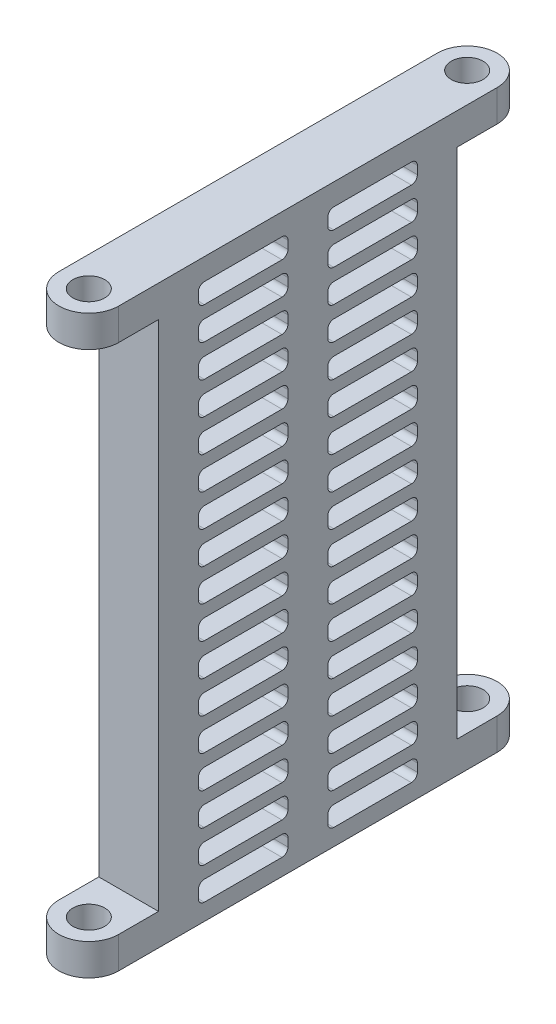
SolidWorks part; units mm, degrees
ref_plane "Front Plane" through (0, 0, 0) normal (0, 0, 1) x (1, 0, 0)
ref_plane "Top Plane" through (0, 0, 0) normal (0, 1, 0) x (1, 0, 0)
ref_plane "Right Plane" through (0, 0, 0) normal (1, 0, 0) x (0, 0, -1)
sketch "Sketch2" plane through (0, 0, 0) normal (0, 1, 0) x (1, 0, 0)
  line L0 (-3, 0) -> (-3, -38)
  line L1 (3, -38) -> (3, 0)
  arc A0 (3, 0) -> (-3, 0) centre (0, 0) ccw
  arc A1 (-3, -38) -> (3, -38) centre (0, -38) ccw
  circle A2 centre (0, 0) radius 1.6
  circle A3 centre (0, -38) radius 1.6
  dimension "D1" = 3.2
  dimension "D2" = 3
  dimension "D3" = 38
extrude "Boss-Extrude1" add sketch "Sketch2" along normal blind 3.175
sketch "Sketch3" plane through (0, 3.175, 0) normal (0, 1, 0) x (1, 0, 0)
  line L0 (-3, 0) -> (-3, -38) construction
  line L1 (-3, -4) -> (3, -4)
  line L2 (-3, -4) -> (-3, -34)
  line L3 (-3, -34) -> (3, -34)
  line L4 (3, -4) -> (3, -34)
  line L5 (3, -38) -> (3, 0) construction
  circle A0 centre (0, -38) radius 1.6 construction
  point P9 (0, -34)
  dimension "D1" = 4
  dimension "D2" = 4
extrude "Boss-Extrude2" add sketch "Sketch3" along normal blind 51.48
ref_plane "Plane1" through (0, 28.915, 0) normal (0, 1, 0) x (1, 0, 0)
mirror "Mirror2" about plane through (0, 28.915, 0) normal (0, 1, 0) of "Boss-Extrude1"
sketch "Sketch4" plane through (3, 0, 0) normal (1, 0, 0) x (0, 0, -1)
  line L0 (-4, 54.655) -> (-34, 54.655) construction
  line L1 (-8.6, 13.4236) -> (-16.4, 13.4236)
  line L2 (-8, 12.8236) -> (-8, 12.0236)
  line L3 (-4, 3.175) -> (-34, 3.175) construction
  line L4 (-8.6, 11.4236) -> (-16.4, 11.4236)
  line L5 (-17, 12.8236) -> (-17, 12.0236)
  line L11 (-19, 57.83) -> (-19, 0) construction
  line L12 (-38, 57.83) -> (0, 57.83) construction
  line L24 (-38, 0) -> (0, 0) construction
  line L25 (-4, 54.655) -> (-4, 3.175) construction
  line L30 (-8.6, 55.655) -> (-16.4, 55.655)
  line L39 (-8, 55.055) -> (-8, 54.255)
  line L40 (-8.6, 53.655) -> (-16.4, 53.655)
  line L41 (-17, 55.055) -> (-17, 54.255)
  line L46 (-8, 55.655) -> (-17, 53.655) construction
  line L47 (-8, 53.655) -> (-17, 55.655) construction
  line L64 (-8.6, 52.4064) -> (-16.4, 52.4064)
  line L69 (-8, 51.8064) -> (-8, 51.0064)
  line L70 (-8.6, 50.4064) -> (-16.4, 50.4064)
  line L71 (-17, 51.8064) -> (-17, 51.0064)
  line L72 (-4, 51.4064) -> (-34, 51.4064) construction
  line L73 (-8, 52.4064) -> (-17, 50.4064) construction
  line L74 (-8, 50.4064) -> (-17, 52.4064) construction
  line L75 (-8.6, 49.1579) -> (-16.4, 49.1579)
  line L76 (-8, 48.5579) -> (-8, 47.7579)
  line L77 (-8.6, 47.1579) -> (-16.4, 47.1579)
  line L78 (-17, 48.5579) -> (-17, 47.7579)
  line L79 (-4, 48.1579) -> (-34, 48.1579) construction
  line L132 (-8, 49.1579) -> (-17, 47.1579) construction
  line L133 (-8, 47.1579) -> (-17, 49.1579) construction
  line L134 (-8.6, 45.9093) -> (-16.4, 45.9093)
  line L135 (-8, 45.3093) -> (-8, 44.5093)
  line L136 (-8.6, 43.9093) -> (-16.4, 43.9093)
  line L137 (-17, 45.3093) -> (-17, 44.5093)
  line L138 (-4, 44.9093) -> (-34, 44.9093) construction
  line L139 (-8, 45.9093) -> (-17, 43.9093) construction
  line L140 (-8, 43.9093) -> (-17, 45.9093) construction
  line L141 (-8.6, 42.6607) -> (-16.4, 42.6607)
  line L142 (-8, 42.0607) -> (-8, 41.2607)
  line L143 (-8.6, 40.6607) -> (-16.4, 40.6607)
  line L144 (-17, 42.0607) -> (-17, 41.2607)
  line L145 (-4, 41.6607) -> (-34, 41.6607) construction
  line L146 (-8, 42.6607) -> (-17, 40.6607) construction
  line L147 (-8, 40.6607) -> (-17, 42.6607) construction
  line L148 (-8.6, 39.4121) -> (-16.4, 39.4121)
  line L149 (-8, 38.8121) -> (-8, 38.0121)
  line L186 (-4, 12.4236) -> (-34, 12.4236) construction
  line L187 (-8, 13.4236) -> (-17, 11.4236) construction
  line L188 (-8, 11.4236) -> (-17, 13.4236) construction
  line L189 (-8.6, 10.175) -> (-16.4, 10.175)
  line L190 (-8, 9.575) -> (-8, 8.775)
  line L191 (-8.6, 8.175) -> (-16.4, 8.175)
  line L192 (-17, 9.575) -> (-17, 8.775)
  line L193 (-4, 9.175) -> (-34, 9.175) construction
  line L194 (-8, 10.175) -> (-17, 8.175) construction
  line L195 (-8, 8.175) -> (-17, 10.175) construction
  line L196 (-30, 1.6779) -> (-21, 3.6779) construction
  line L197 (-30, 3.6779) -> (-21, 1.6779) construction
  line L198 (-30, 4.9264) -> (-21, 6.9264) construction
  line L199 (-30, 6.9264) -> (-21, 4.9264) construction
  line L200 (-30, 14.6721) -> (-21, 16.6721) construction
  line L201 (-8.6, 37.4121) -> (-16.4, 37.4121)
  line L202 (-17, 38.8121) -> (-17, 38.0121)
  line L203 (-4, 38.4121) -> (-34, 38.4121) construction
  line L204 (-8, 39.4121) -> (-17, 37.4121) construction
  line L205 (-8, 37.4121) -> (-17, 39.4121) construction
  line L206 (-8.6, 36.1636) -> (-16.4, 36.1636)
  line L207 (-8, 35.5636) -> (-8, 34.7636)
  line L208 (-8.6, 34.1636) -> (-16.4, 34.1636)
  line L209 (-17, 35.5636) -> (-17, 34.7636)
  line L210 (-4, 35.1636) -> (-34, 35.1636) construction
  line L211 (-8, 36.1636) -> (-17, 34.1636) construction
  line L212 (-8, 34.1636) -> (-17, 36.1636) construction
  line L213 (-8.6, 32.915) -> (-16.4, 32.915)
  line L214 (-8, 32.315) -> (-8, 31.515)
  line L215 (-8.6, 30.915) -> (-16.4, 30.915)
  line L216 (-17, 32.315) -> (-17, 31.515)
  line L217 (-4, 31.915) -> (-34, 31.915) construction
  line L218 (-8, 32.915) -> (-17, 30.915) construction
  line L219 (-8, 30.915) -> (-17, 32.915) construction
  line L220 (-8.6, 29.6664) -> (-16.4, 29.6664)
  line L221 (-8, 29.0664) -> (-8, 28.2664)
  line L222 (-8.6, 27.6664) -> (-16.4, 27.6664)
  line L223 (-17, 29.0664) -> (-17, 28.2664)
  line L224 (-4, 28.6664) -> (-34, 28.6664) construction
  line L225 (-8, 29.6664) -> (-17, 27.6664) construction
  line L226 (-8, 27.6664) -> (-17, 29.6664) construction
  line L227 (-8.6, 26.4179) -> (-16.4, 26.4179)
  line L228 (-8, 25.8179) -> (-8, 25.0179)
  line L229 (-8.6, 24.4179) -> (-16.4, 24.4179)
  line L230 (-17, 25.8179) -> (-17, 25.0179)
  line L231 (-4, 25.4179) -> (-34, 25.4179) construction
  line L232 (-8, 26.4179) -> (-17, 24.4179) construction
  line L233 (-8, 24.4179) -> (-17, 26.4179) construction
  line L234 (-8.6, 23.1693) -> (-16.4, 23.1693)
  line L235 (-8, 22.5693) -> (-8, 21.7693)
  line L236 (-8.6, 21.1693) -> (-16.4, 21.1693)
  line L237 (-17, 22.5693) -> (-17, 21.7693)
  line L238 (-4, 22.1693) -> (-34, 22.1693) construction
  line L239 (-8, 23.1693) -> (-17, 21.1693) construction
  line L240 (-8, 21.1693) -> (-17, 23.1693) construction
  line L241 (-8.6, 19.9207) -> (-16.4, 19.9207)
  line L242 (-8, 19.3207) -> (-8, 18.5207)
  line L243 (-8.6, 17.9207) -> (-16.4, 17.9207)
  line L244 (-17, 19.3207) -> (-17, 18.5207)
  line L245 (-4, 18.9207) -> (-34, 18.9207) construction
  line L246 (-8, 19.9207) -> (-17, 17.9207) construction
  line L247 (-8, 17.9207) -> (-17, 19.9207) construction
  line L248 (-8.6, 16.6721) -> (-16.4, 16.6721)
  line L249 (-8, 16.0721) -> (-8, 15.2721)
  line L250 (-8.6, 14.6721) -> (-16.4, 14.6721)
  line L251 (-17, 16.0721) -> (-17, 15.2721)
  line L252 (-4, 15.6721) -> (-34, 15.6721) construction
  line L253 (-8, 16.6721) -> (-17, 14.6721) construction
  line L254 (-8, 14.6721) -> (-17, 16.6721) construction
  line L255 (-30, 16.6721) -> (-21, 14.6721) construction
  line L256 (-30, 17.9207) -> (-21, 19.9207) construction
  line L257 (-30, 19.9207) -> (-21, 17.9207) construction
  line L258 (-30, 21.1693) -> (-21, 23.1693) construction
  line L259 (-30, 23.1693) -> (-21, 21.1693) construction
  line L260 (-30, 24.4179) -> (-21, 26.4179) construction
  line L261 (-30, 26.4179) -> (-21, 24.4179) construction
  line L262 (-30, 27.6664) -> (-21, 29.6664) construction
  line L263 (-30, 29.6664) -> (-21, 27.6664) construction
  line L264 (-30, 30.915) -> (-21, 32.915) construction
  line L265 (-30, 32.915) -> (-21, 30.915) construction
  line L266 (-30, 34.1636) -> (-21, 36.1636) construction
  line L267 (-30, 36.1636) -> (-21, 34.1636) construction
  line L268 (-30, 37.4121) -> (-21, 39.4121) construction
  line L269 (-30, 39.4121) -> (-21, 37.4121) construction
  line L270 (-30, 8.175) -> (-21, 10.175) construction
  line L271 (-30, 10.175) -> (-21, 8.175) construction
  line L272 (-30, 11.4236) -> (-21, 13.4236) construction
  line L273 (-30, 13.4236) -> (-21, 11.4236) construction
  line L274 (-30, 40.6607) -> (-21, 42.6607) construction
  line L275 (-30, 42.6607) -> (-21, 40.6607) construction
  line L276 (-30, 43.9093) -> (-21, 45.9093) construction
  line L277 (-30, 45.9093) -> (-21, 43.9093) construction
  line L278 (-30, 47.1579) -> (-21, 49.1579) construction
  line L279 (-30, 49.1579) -> (-21, 47.1579) construction
  line L392 (-8.6, 6.9264) -> (-16.4, 6.9264)
  line L393 (-8, 6.3264) -> (-8, 5.5264)
  line L394 (-8.6, 4.9264) -> (-16.4, 4.9264)
  line L395 (-17, 6.3264) -> (-17, 5.5264)
  line L396 (-4, 5.9264) -> (-34, 5.9264) construction
  line L397 (-8, 6.9264) -> (-17, 4.9264) construction
  line L398 (-8, 4.9264) -> (-17, 6.9264) construction
  line L399 (-8.6, 3.6779) -> (-16.4, 3.6779)
  line L400 (-8, 3.0779) -> (-8, 2.2779)
  line L401 (-8.6, 1.6779) -> (-16.4, 1.6779)
  line L402 (-17, 3.0779) -> (-17, 2.2779)
  line L403 (-4, 2.6779) -> (-34, 2.6779) construction
  line L404 (-8, 3.6779) -> (-17, 1.6779) construction
  line L405 (-8, 1.6779) -> (-17, 3.6779) construction
  line L406 (-30, 50.4064) -> (-21, 52.4064) construction
  line L407 (-30, 52.4064) -> (-21, 50.4064) construction
  line L408 (-30, 53.655) -> (-21, 55.655) construction
  line L409 (-30, 55.655) -> (-21, 53.655) construction
  line L410 (-21, 3.0779) -> (-21, 2.2779)
  line L411 (-29.4, 1.6779) -> (-21.6, 1.6779)
  line L412 (-30, 3.0779) -> (-30, 2.2779)
  line L413 (-29.4, 3.6779) -> (-21.6, 3.6779)
  line L414 (-21, 6.3264) -> (-21, 5.5264)
  line L415 (-29.4, 4.9264) -> (-21.6, 4.9264)
  line L416 (-30, 6.3264) -> (-30, 5.5264)
  line L417 (-29.4, 6.9264) -> (-21.6, 6.9264)
  line L418 (-21, 16.0721) -> (-21, 15.2721)
  line L419 (-29.4, 14.6721) -> (-21.6, 14.6721)
  line L420 (-30, 16.0721) -> (-30, 15.2721)
  line L421 (-29.4, 16.6721) -> (-21.6, 16.6721)
  line L422 (-21, 19.3207) -> (-21, 18.5207)
  line L423 (-29.4, 17.9207) -> (-21.6, 17.9207)
  line L424 (-30, 19.3207) -> (-30, 18.5207)
  line L425 (-29.4, 19.9207) -> (-21.6, 19.9207)
  line L426 (-21, 22.5693) -> (-21, 21.7693)
  line L427 (-29.4, 21.1693) -> (-21.6, 21.1693)
  line L428 (-30, 22.5693) -> (-30, 21.7693)
  line L429 (-29.4, 23.1693) -> (-21.6, 23.1693)
  line L430 (-21, 25.8179) -> (-21, 25.0179)
  line L431 (-29.4, 24.4179) -> (-21.6, 24.4179)
  line L432 (-30, 25.8179) -> (-30, 25.0179)
  line L433 (-29.4, 26.4179) -> (-21.6, 26.4179)
  line L434 (-21, 29.0664) -> (-21, 28.2664)
  line L435 (-29.4, 27.6664) -> (-21.6, 27.6664)
  line L436 (-30, 29.0664) -> (-30, 28.2664)
  line L437 (-29.4, 29.6664) -> (-21.6, 29.6664)
  line L438 (-21, 32.315) -> (-21, 31.515)
  line L439 (-29.4, 30.915) -> (-21.6, 30.915)
  line L440 (-30, 32.315) -> (-30, 31.515)
  line L441 (-29.4, 32.915) -> (-21.6, 32.915)
  line L442 (-21, 35.5636) -> (-21, 34.7636)
  line L443 (-29.4, 34.1636) -> (-21.6, 34.1636)
  line L444 (-30, 35.5636) -> (-30, 34.7636)
  line L445 (-29.4, 36.1636) -> (-21.6, 36.1636)
  line L446 (-21, 38.8121) -> (-21, 38.0121)
  line L447 (-29.4, 37.4121) -> (-21.6, 37.4121)
  line L448 (-21, 9.575) -> (-21, 8.775)
  line L449 (-29.4, 8.175) -> (-21.6, 8.175)
  line L450 (-30, 9.575) -> (-30, 8.775)
  line L451 (-29.4, 10.175) -> (-21.6, 10.175)
  line L452 (-30, 38.8121) -> (-30, 38.0121)
  line L453 (-29.4, 39.4121) -> (-21.6, 39.4121)
  line L454 (-21, 42.0607) -> (-21, 41.2607)
  line L455 (-29.4, 40.6607) -> (-21.6, 40.6607)
  line L456 (-30, 42.0607) -> (-30, 41.2607)
  line L457 (-29.4, 42.6607) -> (-21.6, 42.6607)
  line L458 (-21, 45.3093) -> (-21, 44.5093)
  line L459 (-29.4, 43.9093) -> (-21.6, 43.9093)
  line L460 (-30, 45.3093) -> (-30, 44.5093)
  line L461 (-29.4, 45.9093) -> (-21.6, 45.9093)
  line L462 (-21, 48.5579) -> (-21, 47.7579)
  line L463 (-29.4, 47.1579) -> (-21.6, 47.1579)
  line L464 (-30, 48.5579) -> (-30, 47.7579)
  line L465 (-29.4, 49.1579) -> (-21.6, 49.1579)
  line L466 (-21, 51.8064) -> (-21, 51.0064)
  line L467 (-29.4, 50.4064) -> (-21.6, 50.4064)
  line L468 (-30, 51.8064) -> (-30, 51.0064)
  line L469 (-29.4, 52.4064) -> (-21.6, 52.4064)
  line L470 (-21, 55.055) -> (-21, 54.255)
  line L471 (-29.4, 53.655) -> (-21.6, 53.655)
  line L472 (-30, 55.055) -> (-30, 54.255)
  line L473 (-29.4, 55.655) -> (-21.6, 55.655)
  line L474 (-21, 12.8236) -> (-21, 12.0236)
  line L475 (-29.4, 11.4236) -> (-21.6, 11.4236)
  line L476 (-30, 12.8236) -> (-30, 12.0236)
  line L477 (-29.4, 13.4236) -> (-21.6, 13.4236)
  arc A72 (-16.4, 13.4236) -> (-17, 12.8236) centre (-16.4, 12.8236) ccw
  arc A73 (-16.4, 11.4236) -> (-17, 12.0236) centre (-16.4, 12.0236) cw
  arc A74 (-8.6, 13.4236) -> (-8, 12.8236) centre (-8.6, 12.8236) cw
  arc A75 (-8, 12.0236) -> (-8.6, 11.4236) centre (-8.6, 12.0236) cw
  arc A76 (-16.4, 55.655) -> (-17, 55.055) centre (-16.4, 55.055) ccw
  arc A77 (-16.4, 53.655) -> (-17, 54.255) centre (-16.4, 54.255) cw
  arc A78 (-8.6, 55.655) -> (-8, 55.055) centre (-8.6, 55.055) cw
  arc A79 (-8, 54.255) -> (-8.6, 53.655) centre (-8.6, 54.255) cw
  arc A80 (-16.4, 52.4064) -> (-17, 51.8064) centre (-16.4, 51.8064) ccw
  arc A81 (-16.4, 50.4064) -> (-17, 51.0064) centre (-16.4, 51.0064) cw
  arc A82 (-8.6, 52.4064) -> (-8, 51.8064) centre (-8.6, 51.8064) cw
  arc A83 (-8, 51.0064) -> (-8.6, 50.4064) centre (-8.6, 51.0064) cw
  arc A84 (-16.4, 49.1579) -> (-17, 48.5579) centre (-16.4, 48.5579) ccw
  arc A85 (-16.4, 47.1579) -> (-17, 47.7579) centre (-16.4, 47.7579) cw
  arc A86 (-8.6, 49.1579) -> (-8, 48.5579) centre (-8.6, 48.5579) cw
  arc A87 (-8, 47.7579) -> (-8.6, 47.1579) centre (-8.6, 47.7579) cw
  arc A88 (-16.4, 45.9093) -> (-17, 45.3093) centre (-16.4, 45.3093) ccw
  arc A89 (-16.4, 43.9093) -> (-17, 44.5093) centre (-16.4, 44.5093) cw
  arc A90 (-8.6, 45.9093) -> (-8, 45.3093) centre (-8.6, 45.3093) cw
  arc A91 (-8, 44.5093) -> (-8.6, 43.9093) centre (-8.6, 44.5093) cw
  arc A92 (-16.4, 42.6607) -> (-17, 42.0607) centre (-16.4, 42.0607) ccw
  arc A93 (-16.4, 40.6607) -> (-17, 41.2607) centre (-16.4, 41.2607) cw
  arc A94 (-8.6, 42.6607) -> (-8, 42.0607) centre (-8.6, 42.0607) cw
  arc A95 (-8, 41.2607) -> (-8.6, 40.6607) centre (-8.6, 41.2607) cw
  arc A96 (-16.4, 39.4121) -> (-17, 38.8121) centre (-16.4, 38.8121) ccw
  arc A97 (-16.4, 37.4121) -> (-17, 38.0121) centre (-16.4, 38.0121) cw
  arc A98 (-8.6, 39.4121) -> (-8, 38.8121) centre (-8.6, 38.8121) cw
  arc A99 (-8, 38.0121) -> (-8.6, 37.4121) centre (-8.6, 38.0121) cw
  arc A100 (-16.4, 36.1636) -> (-17, 35.5636) centre (-16.4, 35.5636) ccw
  arc A101 (-16.4, 34.1636) -> (-17, 34.7636) centre (-16.4, 34.7636) cw
  arc A102 (-8.6, 36.1636) -> (-8, 35.5636) centre (-8.6, 35.5636) cw
  arc A103 (-8, 34.7636) -> (-8.6, 34.1636) centre (-8.6, 34.7636) cw
  arc A104 (-16.4, 32.915) -> (-17, 32.315) centre (-16.4, 32.315) ccw
  arc A105 (-16.4, 30.915) -> (-17, 31.515) centre (-16.4, 31.515) cw
  arc A106 (-8.6, 32.915) -> (-8, 32.315) centre (-8.6, 32.315) cw
  arc A107 (-8, 31.515) -> (-8.6, 30.915) centre (-8.6, 31.515) cw
  arc A108 (-16.4, 29.6664) -> (-17, 29.0664) centre (-16.4, 29.0664) ccw
  arc A109 (-16.4, 27.6664) -> (-17, 28.2664) centre (-16.4, 28.2664) cw
  arc A110 (-8.6, 29.6664) -> (-8, 29.0664) centre (-8.6, 29.0664) cw
  arc A111 (-8, 28.2664) -> (-8.6, 27.6664) centre (-8.6, 28.2664) cw
  arc A112 (-16.4, 26.4179) -> (-17, 25.8179) centre (-16.4, 25.8179) ccw
  arc A113 (-16.4, 24.4179) -> (-17, 25.0179) centre (-16.4, 25.0179) cw
  arc A114 (-8.6, 26.4179) -> (-8, 25.8179) centre (-8.6, 25.8179) cw
  arc A115 (-8, 25.0179) -> (-8.6, 24.4179) centre (-8.6, 25.0179) cw
  arc A116 (-16.4, 23.1693) -> (-17, 22.5693) centre (-16.4, 22.5693) ccw
  arc A117 (-16.4, 21.1693) -> (-17, 21.7693) centre (-16.4, 21.7693) cw
  arc A118 (-8.6, 23.1693) -> (-8, 22.5693) centre (-8.6, 22.5693) cw
  arc A119 (-8, 21.7693) -> (-8.6, 21.1693) centre (-8.6, 21.7693) cw
  arc A120 (-16.4, 19.9207) -> (-17, 19.3207) centre (-16.4, 19.3207) ccw
  arc A121 (-16.4, 17.9207) -> (-17, 18.5207) centre (-16.4, 18.5207) cw
  arc A122 (-8.6, 19.9207) -> (-8, 19.3207) centre (-8.6, 19.3207) cw
  arc A123 (-8, 18.5207) -> (-8.6, 17.9207) centre (-8.6, 18.5207) cw
  arc A124 (-16.4, 16.6721) -> (-17, 16.0721) centre (-16.4, 16.0721) ccw
  arc A125 (-16.4, 14.6721) -> (-17, 15.2721) centre (-16.4, 15.2721) cw
  arc A126 (-8.6, 16.6721) -> (-8, 16.0721) centre (-8.6, 16.0721) cw
  arc A127 (-8, 15.2721) -> (-8.6, 14.6721) centre (-8.6, 15.2721) cw
  arc A180 (-16.4, 10.175) -> (-17, 9.575) centre (-16.4, 9.575) ccw
  arc A181 (-16.4, 8.175) -> (-17, 8.775) centre (-16.4, 8.775) cw
  arc A182 (-8.6, 10.175) -> (-8, 9.575) centre (-8.6, 9.575) cw
  arc A183 (-8, 8.775) -> (-8.6, 8.175) centre (-8.6, 8.775) cw
  arc A244 (-16.4, 6.9264) -> (-17, 6.3264) centre (-16.4, 6.3264) ccw
  arc A245 (-16.4, 4.9264) -> (-17, 5.5264) centre (-16.4, 5.5264) cw
  arc A246 (-8.6, 6.9264) -> (-8, 6.3264) centre (-8.6, 6.3264) cw
  arc A247 (-8, 5.5264) -> (-8.6, 4.9264) centre (-8.6, 5.5264) cw
  arc A248 (-16.4, 3.6779) -> (-17, 3.0779) centre (-16.4, 3.0779) ccw
  arc A249 (-16.4, 1.6779) -> (-17, 2.2779) centre (-16.4, 2.2779) cw
  arc A250 (-8.6, 3.6779) -> (-8, 3.0779) centre (-8.6, 3.0779) cw
  arc A251 (-8, 2.2779) -> (-8.6, 1.6779) centre (-8.6, 2.2779) cw
  arc A252 (-30, 2.2779) -> (-29.4, 1.6779) centre (-29.4, 2.2779) ccw
  arc A253 (-29.4, 3.6779) -> (-30, 3.0779) centre (-29.4, 3.0779) ccw
  arc A254 (-21.6, 1.6779) -> (-21, 2.2779) centre (-21.6, 2.2779) ccw
  arc A255 (-21.6, 3.6779) -> (-21, 3.0779) centre (-21.6, 3.0779) cw
  arc A256 (-30, 5.5264) -> (-29.4, 4.9264) centre (-29.4, 5.5264) ccw
  arc A257 (-29.4, 6.9264) -> (-30, 6.3264) centre (-29.4, 6.3264) ccw
  arc A258 (-21.6, 4.9264) -> (-21, 5.5264) centre (-21.6, 5.5264) ccw
  arc A259 (-21.6, 6.9264) -> (-21, 6.3264) centre (-21.6, 6.3264) cw
  arc A260 (-30, 8.775) -> (-29.4, 8.175) centre (-29.4, 8.775) ccw
  arc A261 (-29.4, 10.175) -> (-30, 9.575) centre (-29.4, 9.575) ccw
  arc A262 (-21.6, 8.175) -> (-21, 8.775) centre (-21.6, 8.775) ccw
  arc A263 (-21.6, 10.175) -> (-21, 9.575) centre (-21.6, 9.575) cw
  arc A264 (-30, 15.2721) -> (-29.4, 14.6721) centre (-29.4, 15.2721) ccw
  arc A265 (-29.4, 16.6721) -> (-30, 16.0721) centre (-29.4, 16.0721) ccw
  arc A266 (-21.6, 14.6721) -> (-21, 15.2721) centre (-21.6, 15.2721) ccw
  arc A267 (-21.6, 16.6721) -> (-21, 16.0721) centre (-21.6, 16.0721) cw
  arc A268 (-30, 18.5207) -> (-29.4, 17.9207) centre (-29.4, 18.5207) ccw
  arc A269 (-29.4, 19.9207) -> (-30, 19.3207) centre (-29.4, 19.3207) ccw
  arc A270 (-21.6, 17.9207) -> (-21, 18.5207) centre (-21.6, 18.5207) ccw
  arc A271 (-21.6, 19.9207) -> (-21, 19.3207) centre (-21.6, 19.3207) cw
  arc A272 (-30, 21.7693) -> (-29.4, 21.1693) centre (-29.4, 21.7693) ccw
  arc A273 (-29.4, 23.1693) -> (-30, 22.5693) centre (-29.4, 22.5693) ccw
  arc A274 (-21.6, 21.1693) -> (-21, 21.7693) centre (-21.6, 21.7693) ccw
  arc A275 (-21.6, 23.1693) -> (-21, 22.5693) centre (-21.6, 22.5693) cw
  arc A276 (-30, 25.0179) -> (-29.4, 24.4179) centre (-29.4, 25.0179) ccw
  arc A277 (-29.4, 26.4179) -> (-30, 25.8179) centre (-29.4, 25.8179) ccw
  arc A278 (-21.6, 24.4179) -> (-21, 25.0179) centre (-21.6, 25.0179) ccw
  arc A279 (-21.6, 26.4179) -> (-21, 25.8179) centre (-21.6, 25.8179) cw
  arc A280 (-30, 28.2664) -> (-29.4, 27.6664) centre (-29.4, 28.2664) ccw
  arc A281 (-29.4, 29.6664) -> (-30, 29.0664) centre (-29.4, 29.0664) ccw
  arc A282 (-21.6, 27.6664) -> (-21, 28.2664) centre (-21.6, 28.2664) ccw
  arc A283 (-21.6, 29.6664) -> (-21, 29.0664) centre (-21.6, 29.0664) cw
  arc A284 (-30, 31.515) -> (-29.4, 30.915) centre (-29.4, 31.515) ccw
  arc A285 (-29.4, 32.915) -> (-30, 32.315) centre (-29.4, 32.315) ccw
  arc A286 (-21.6, 30.915) -> (-21, 31.515) centre (-21.6, 31.515) ccw
  arc A287 (-21.6, 32.915) -> (-21, 32.315) centre (-21.6, 32.315) cw
  arc A288 (-30, 34.7636) -> (-29.4, 34.1636) centre (-29.4, 34.7636) ccw
  arc A289 (-29.4, 36.1636) -> (-30, 35.5636) centre (-29.4, 35.5636) ccw
  arc A290 (-21.6, 34.1636) -> (-21, 34.7636) centre (-21.6, 34.7636) ccw
  arc A291 (-21.6, 36.1636) -> (-21, 35.5636) centre (-21.6, 35.5636) cw
  arc A292 (-30, 38.0121) -> (-29.4, 37.4121) centre (-29.4, 38.0121) ccw
  arc A293 (-29.4, 39.4121) -> (-30, 38.8121) centre (-29.4, 38.8121) ccw
  arc A294 (-21.6, 37.4121) -> (-21, 38.0121) centre (-21.6, 38.0121) ccw
  arc A295 (-21.6, 39.4121) -> (-21, 38.8121) centre (-21.6, 38.8121) cw
  arc A296 (-30, 41.2607) -> (-29.4, 40.6607) centre (-29.4, 41.2607) ccw
  arc A297 (-29.4, 42.6607) -> (-30, 42.0607) centre (-29.4, 42.0607) ccw
  arc A298 (-21.6, 40.6607) -> (-21, 41.2607) centre (-21.6, 41.2607) ccw
  arc A299 (-21.6, 42.6607) -> (-21, 42.0607) centre (-21.6, 42.0607) cw
  arc A300 (-30, 44.5093) -> (-29.4, 43.9093) centre (-29.4, 44.5093) ccw
  arc A301 (-29.4, 45.9093) -> (-30, 45.3093) centre (-29.4, 45.3093) ccw
  arc A302 (-21.6, 43.9093) -> (-21, 44.5093) centre (-21.6, 44.5093) ccw
  arc A303 (-21.6, 45.9093) -> (-21, 45.3093) centre (-21.6, 45.3093) cw
  arc A304 (-30, 47.7579) -> (-29.4, 47.1579) centre (-29.4, 47.7579) ccw
  arc A305 (-29.4, 49.1579) -> (-30, 48.5579) centre (-29.4, 48.5579) ccw
  arc A306 (-21.6, 47.1579) -> (-21, 47.7579) centre (-21.6, 47.7579) ccw
  arc A307 (-21.6, 49.1579) -> (-21, 48.5579) centre (-21.6, 48.5579) cw
  arc A308 (-30, 51.0064) -> (-29.4, 50.4064) centre (-29.4, 51.0064) ccw
  arc A309 (-29.4, 52.4064) -> (-30, 51.8064) centre (-29.4, 51.8064) ccw
  arc A310 (-21.6, 50.4064) -> (-21, 51.0064) centre (-21.6, 51.0064) ccw
  arc A311 (-21.6, 52.4064) -> (-21, 51.8064) centre (-21.6, 51.8064) cw
  arc A312 (-30, 54.255) -> (-29.4, 53.655) centre (-29.4, 54.255) ccw
  arc A313 (-29.4, 55.655) -> (-30, 55.055) centre (-29.4, 55.055) ccw
  arc A314 (-21.6, 53.655) -> (-21, 54.255) centre (-21.6, 54.255) ccw
  arc A315 (-21.6, 55.655) -> (-21, 55.055) centre (-21.6, 55.055) cw
  arc A316 (-30, 12.0236) -> (-29.4, 11.4236) centre (-29.4, 12.0236) ccw
  arc A317 (-29.4, 13.4236) -> (-30, 12.8236) centre (-29.4, 12.8236) ccw
  arc A318 (-21.6, 11.4236) -> (-21, 12.0236) centre (-21.6, 12.0236) ccw
  arc A319 (-21.6, 13.4236) -> (-21, 12.8236) centre (-21.6, 12.8236) cw
  point P10 (-12.5, 54.655)
  point P13 (-14.25, 34.325)
  point P14 (-14.25, 31.825)
  point P15 (-14.25, 29.325)
  point P16 (-14.25, 26.825)
  point P36 (-12.5, 51.4064)
  point P55 (-12.5, 48.1579)
  point P74 (-12.5, 44.9093)
  point P93 (-12.5, 41.6607)
  point P112 (-12.5, 38.4121)
  point P131 (-12.5, 35.1636)
  point P150 (-12.5, 31.915)
  point P169 (-12.5, 28.6664)
  point P188 (-12.5, 25.4179)
  point P207 (-12.5, 22.1693)
  point P226 (-12.5, 18.9207)
  point P245 (-12.5, 15.6721)
  point P328 (-12.5, 12.4236)
  point P347 (-12.5, 9.175)
  point P560 (-12.5, 5.9264)
  point P579 (-12.5, 2.6779)
  point P613 (-25.5, 2.6779)
  point P614 (-25.5, 5.9264)
  point P615 (-25.5, 9.175)
  point P616 (-25.5, 12.4236)
  point P617 (-25.5, 15.6721)
  point P618 (-25.5, 18.9207)
  point P619 (-25.5, 22.1693)
  point P620 (-25.5, 25.4179)
  point P621 (-25.5, 28.6664)
  point P622 (-25.5, 31.915)
  point P623 (-25.5, 35.1636)
  point P624 (-25.5, 38.4121)
  point P625 (-25.5, 41.6607)
  point P626 (-25.5, 44.9093)
  point P627 (-25.5, 48.1579)
  point P628 (-25.5, 51.4064)
  point P629 (-25.5, 54.655)
  dimension "D6" = 1.2486
  dimension "D4" = 0.6
  dimension "D1" = 2
  dimension "D2" = 4
  dimension "D3" = 2
  dimension "D5" = 17
extrude "Cut-Extrude1" cut sketch "Sketch4" against normal through all
equation "\"D2@Sketch3\"=\"D1@Sketch3\""
